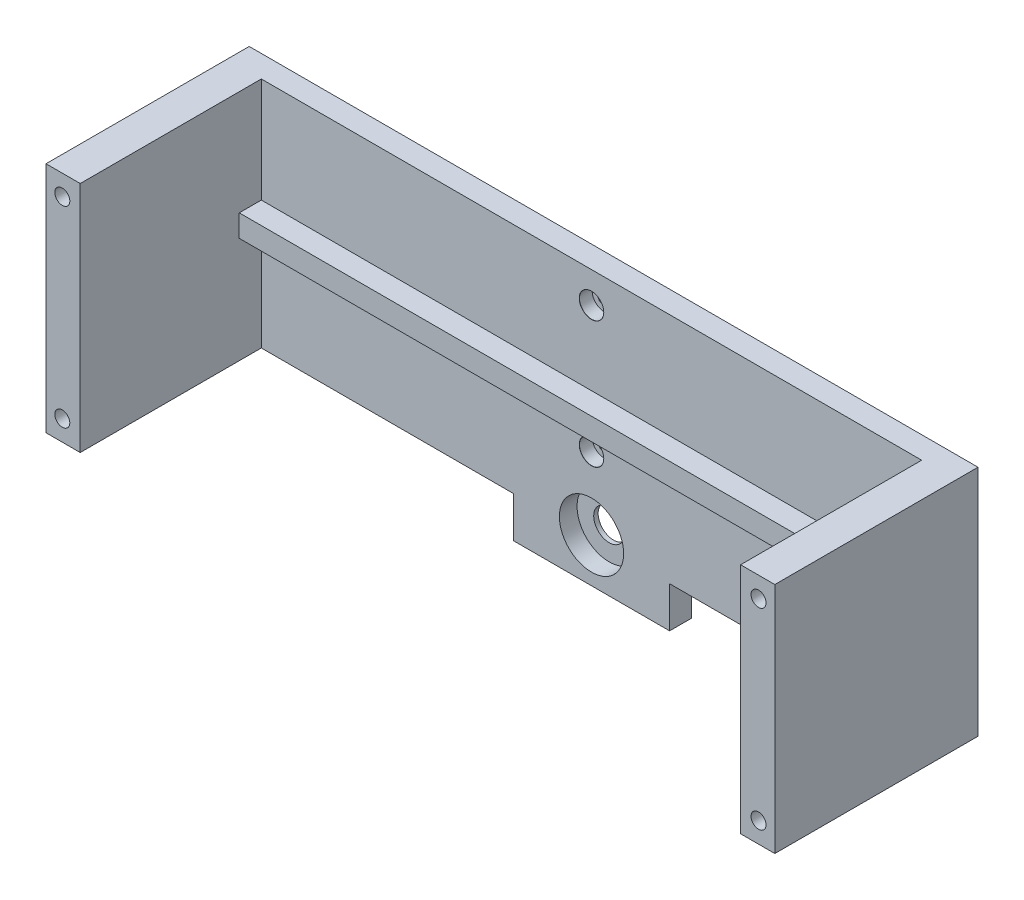
SolidWorks part; units mm, degrees
ref_plane "Plan de face" through (0, 0, 0) normal (0, 0, 1) x (1, 0, 0)
ref_plane "Plan de dessus" through (0, 0, 0) normal (0, 1, 0) x (1, 0, 0)
ref_plane "Plan de droite" through (0, 0, 0) normal (1, 0, 0) x (0, 0, -1)
sketch "Esquisse1" plane through (0, 0, 0) normal (0, 0, 1) x (1, 0, 0)
  line L1 (-30.9078, 20.7742) -> (134.0922, 20.7742)
  line L2 (-30.9078, 20.7742) -> (-30.9078, -31.9758)
  line L3 (-30.9078, -31.9758) -> (134.0922, -31.9758)
  line L4 (134.0922, 20.7742) -> (134.0922, -31.9758)
  dimension "D1" = 52.75
  dimension "D2" = 165
extrude "Boss.-Extru.1" add sketch "Esquisse1" along normal blind 5
sketch "Esquisse2" plane through (0, 0, 5) normal (0, 0, 1) x (1, 0, 0)
  line L0 (-30.9078, -31.9758) -> (134.0922, -31.9758) construction
  line L1 (-30.9078, 20.7742) -> (-23.1578, 20.7742)
  line L2 (-30.9078, 20.7742) -> (-30.9078, -31.9758)
  line L3 (-30.9078, -31.9758) -> (-23.1578, -31.9758)
  line L4 (-23.1578, 20.7742) -> (-23.1578, -2.9758)
  line L5 (-23.1578, -7.9758) -> (126.3422, -7.9758)
  line L6 (134.0922, 20.7742) -> (126.3422, 20.7742)
  line L7 (134.0922, 20.7742) -> (134.0922, -31.9758)
  line L8 (134.0922, -31.9758) -> (126.3422, -31.9758)
  line L9 (126.3422, 20.7742) -> (126.3422, -2.9758)
  line L10 (-23.1578, -2.9758) -> (126.3422, -2.9758)
  line L14 (-23.1578, -7.9758) -> (-23.1578, -31.9758)
  line L15 (126.3422, -7.9758) -> (126.3422, -31.9758)
  dimension "D1" = 7.75
  dimension "D2" = 7.75
  dimension "D3" = 5
  dimension "D4" = 24
extrude "Boss.-Extru.2" add sketch "Esquisse2" along normal blind 41
sketch "Esquisse3" plane through (0, 0, 46) normal (0, 0, 1) x (1, 0, 0)
  line L1 (-23.1578, -2.9758) -> (126.3422, -2.9758)
  line L2 (-23.1578, -2.9758) -> (-23.1578, -7.9758)
  line L3 (-23.1578, -7.9758) -> (126.3422, -7.9758)
  line L4 (126.3422, -2.9758) -> (126.3422, -7.9758)
extrude "Enlèv. mat.-Extru.1" cut sketch "Esquisse3" against normal blind 36
sketch "Sketch3" plane through (0, 0, 46) normal (0, 0, 1) x (1, 0, 0)
  line L0 (-30.9078, -5.6008) -> (144.633, -5.6008) construction
  line L1 (-30.9078, 20.7742) -> (-30.9078, -31.9758) construction
  line L4 (51.5922, 20.7742) -> (51.5922, -31.9758) construction
  line L5 (126.3422, 20.7742) -> (-23.1578, 20.7742) construction
  line L6 (-23.1578, -31.9758) -> (126.3422, -31.9758) construction
  point P0 (-27.2209, 16.1492)
  point P29 (130.4053, 16.1492)
  point P30 (130.4053, -27.3508)
  point P31 (-27.2209, -27.3508)
  dimension "D1" = 43.5
hole_wizard "Dégagement M31" positions "Sketch3" profile "Sketch2" hole size "M3" standard "ISO"
sketch "Sketch2" plane through (-27.2209, 16.1492, 46) normal (1, 0, 0) x (0, -1, 0)
  line L0 (0, 0) -> (0, 7.0215)
  line L1 (0, 7.0215) -> (1.7, 6)
  line L2 (1.7, 6) -> (1.7, 0)
  line L5 (1.7, 0) -> (0, 0)
  line L10 (0, 7.0215) -> (-1.7, 6) construction
  line L11 (0, -6.35) -> (0, 107.95) construction
  dimension "Hole Dia." = 3.4
  dimension "Hole Depth" = 6
  dimension "Drill Angle" = 118
sketch "Sketch6" plane through (0, 0, 5) normal (0, 0, 1) x (1, 0, 0)
  line L0 (126.3422, 20.7742) -> (-23.1578, 20.7742) construction
  point P20 (51.5922, 13.7742)
  point P22 (51.5922, -14.9258)
  point P26 (51.5922, 20.7742)
  dimension "D1" = 7
  dimension "D2" = 28.7
hole_wizard "Chambrage pour vis à six pans creux M2.51" positions "Sketch6" profile "Sketch5" counterbore size "M2.5" standard "ISO" end condition through all
sketch "Sketch5" plane through (51.5922, 13.7742, 5) normal (1, 0, 0) x (0, -1, 0)
  line L0 (0, 0) -> (0, 5)
  line L1 (0, 5) -> (1.55, 5)
  line L3 (1.55, 5) -> (1.55, 2.9)
  line L4 (2.75, 2.9) -> (1.55, 2.9)
  line L5 (2.75, 2.9) -> (2.75, 0.025)
  line L6 (2.75, 0.025) -> (2.775, 0)
  line L7 (2.775, 0) -> (0, 0)
  line L8 (-2.75, 0.025) -> (-2.775, 0) construction
  line L11 (0, -6.35) -> (0, 107.95) construction
  dimension "Thru Hole Dia." = 3.1
  dimension "Thru Hole Depth" = 5
  dimension "C'Bore Dia." = 5.5
  dimension "C'Bore Depth" = 2.9
  dimension "Near C'Sink Dia." = 5.55
  dimension "Near C'Sink Angle" = 90
sketch "Sketch7" plane through (0, -31.9758, 0) normal (0, -1, 0) x (1, 0, 0)
  line L7 (-23.1578, 5) -> (126.3422, 5) construction
  line L8 (69.2722, 5) -> (33.9122, 5)
  line L9 (69.2722, 5) -> (69.2722, 0)
  line L10 (69.2722, 0) -> (33.9122, 0)
  line L11 (33.9122, 5) -> (33.9122, 0)
  line L12 (-30.9078, 0) -> (134.0922, 0) construction
  line L14 (-23.1578, 5) -> (126.3422, 5) construction
  point P10 (51.5922, 5)
  point P11 (51.5922, 5)
  dimension "D1" = 35.36
extrude "Boss-Extrude1" add sketch "Sketch7" along normal up to vertex (9.25 mm away)
sketch "Sketch10" plane through (0, 0, 5) normal (0, 0, 1) x (1, 0, 0)
  line L0 (33.9122, -41.2258) -> (69.2722, -41.2258) construction
  point P0 (51.5922, -31.2758)
  point P9 (51.5922, -41.2258)
hole_wizard "Chambrage pour vis à tête hexagonale M61" positions "Sketch10" profile "Sketch9" counterbore size "M6" standard "ISO" end condition through all
sketch "Sketch9" plane through (51.5922, -31.2758, 5) normal (1, 0, 0) x (0, -1, 0)
  line L0 (0, 0) -> (0, 5)
  line L1 (0, 5) -> (3.5, 5)
  line L3 (3.5, 5) -> (3.5, 4)
  line L4 (3.5, 4) -> (7.2735, 4)
  line L5 (7.2735, 4) -> (7.2735, 0)
  line L7 (7.2735, 0) -> (0, 0)
  line L11 (0, -6.35) -> (0, 107.95) construction
  dimension "Thru Hole Dia." = 7
  dimension "Thru Hole Depth" = 5
  dimension "C'Bore Dia." = 14.547
  dimension "C'Bore Depth" = 4
